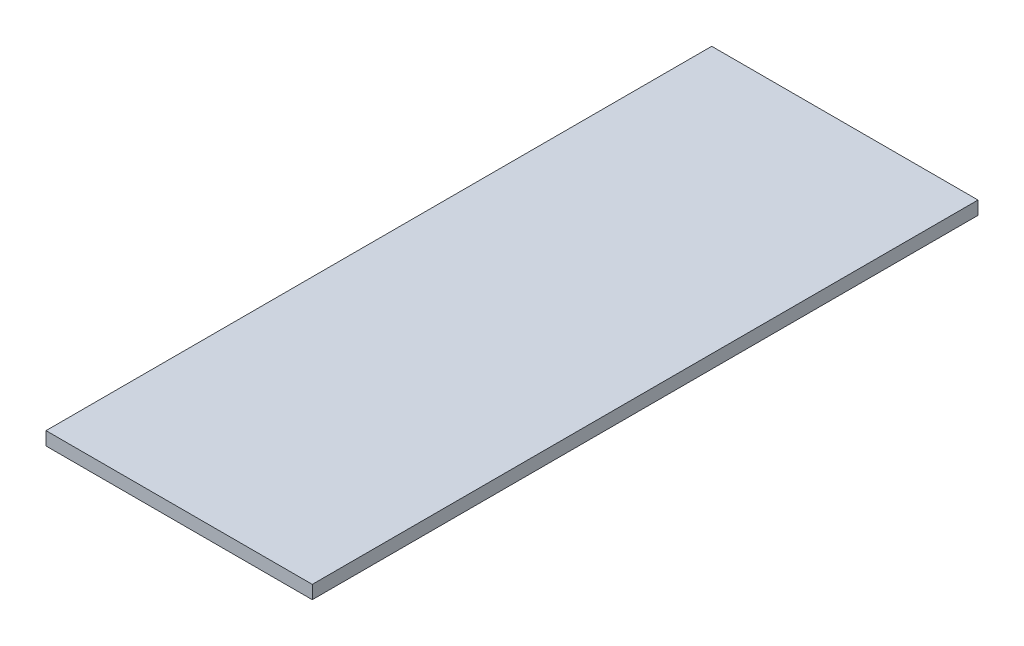
SolidWorks part; units mm, degrees
ref_plane "Plano frontal" through (0, 0, 0) normal (0, 0, 1) x (1, 0, 0)
ref_plane "Plano superior" through (0, 0, 0) normal (0, 1, 0) x (1, 0, 0)
ref_plane "Plano direito" through (0, 0, 0) normal (1, 0, 0) x (0, 0, -1)
sketch "Esboço1" plane through (0, 0, 0) normal (0, 1, 0) x (1, 0, 0)
  line L1 (-10, -25) -> (10, -25)
  line L2 (-10, -25) -> (-10, 25)
  line L3 (-10, 25) -> (10, 25)
  line L4 (10, -25) -> (10, 25)
  line L5 (-10, -25) -> (10, 25) construction
  line L6 (-10, 25) -> (10, -25) construction
  point P0 (0, 0)
  dimension "D1" = 20
  dimension "D2" = 50
extrude "Ressalto-extrusão1" add sketch "Esboço1" along normal blind 1
